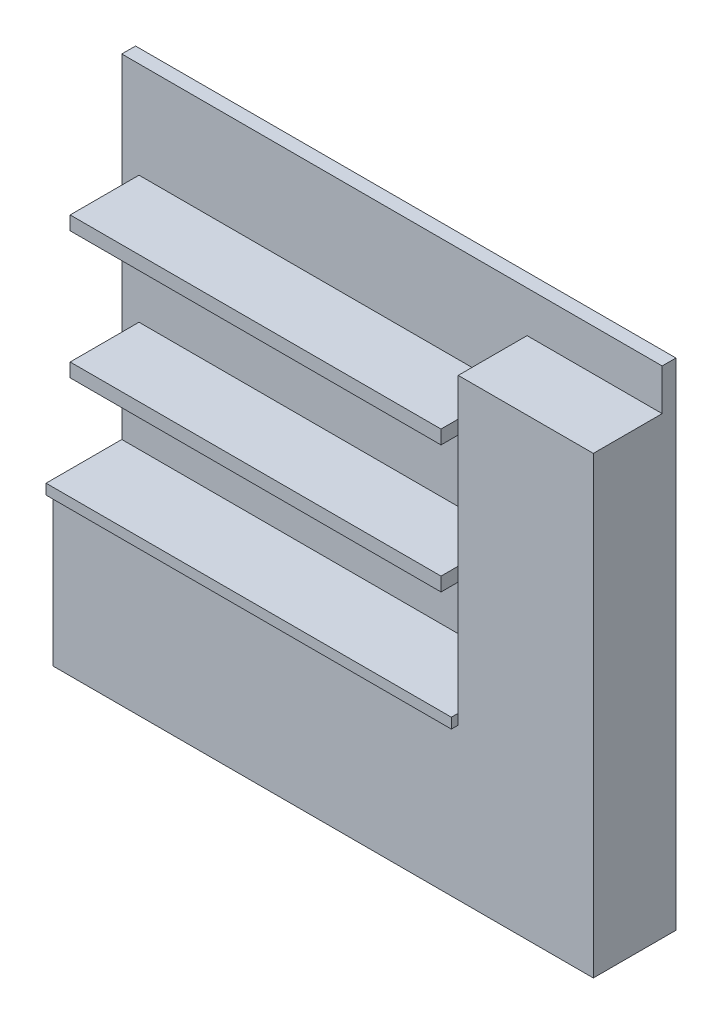
SolidWorks part; units mm, degrees
ref_plane "Front Plane" through (0, 0, 0) normal (0, 0, 1) x (1, 0, 0)
ref_plane "Top Plane" through (0, 0, 0) normal (0, 1, 0) x (1, 0, 0)
ref_plane "Right Plane" through (0, 0, 0) normal (1, 0, 0) x (0, 0, -1)
sketch "Sketch1" plane through (0, 0, 0) normal (0, 0, 1) x (1, 0, 0)
  line L1 (-1993.9, 1828.8) -> (1993.9, 1828.8)
  line L2 (-1993.9, 1828.8) -> (-1993.9, -1828.8)
  line L3 (-1993.9, -1828.8) -> (1993.9, -1828.8)
  line L4 (1993.9, 1828.8) -> (1993.9, -1828.8)
  line L5 (-1993.9, 1828.8) -> (1993.9, -1828.8) construction
  line L6 (-1993.9, -1828.8) -> (1993.9, 1828.8) construction
  point P4 (0, 0)
  dimension "D1" = 3657.6
  dimension "D2" = 3987.8
extrude "Boss-Extrude1" add sketch "Sketch1" along normal blind 101.6
sketch "Sketch2" plane through (0, 0, 101.6) normal (0, 0, 1) x (1, 0, 0)
  line L0 (-1993.9, -1828.8) -> (-1993.9, -711.2)
  line L1 (-1993.9, 1828.8) -> (-1993.9, -1828.8) construction
  line L2 (-1993.9, -711.2) -> (996.95, -711.2)
  line L3 (996.95, -711.2) -> (996.95, 1524)
  line L4 (996.95, 1524) -> (1993.9, 1524)
  line L5 (1993.9, -1828.8) -> (1993.9, 1828.8) construction
  line L6 (1993.9, 1524) -> (1993.9, -1828.8)
  line L7 (1993.9, -1828.8) -> (-1993.9, -1828.8)
  dimension "D1" = 3352.8
  dimension "D2" = 996.95
  dimension "D3" = 1117.6
extrude "Boss-Extrude2" add sketch "Sketch2" along normal blind 508
sketch "Sketch3" plane through (0, 0, 609.6) normal (0, 0, 1) x (1, 0, 0)
  line L0 (-1993.9, -711.2) -> (-1231.9, -711.2)
  line L1 (996.95, -711.2) -> (996.95, -1828.8)
  line L2 (-1993.9, -1828.8) -> (1993.9, -1828.8) construction
  line L3 (-1993.9, -711.2) -> (-1993.9, -1828.8)
  line L4 (-1993.9, -711.2) -> (-1993.9, -1828.8) construction
  line L5 (-1993.9, -1828.8) -> (-1231.9, -1828.8)
  line L6 (-1231.9, -1828.8) -> (-1231.9, -711.2)
  line L7 (-1231.9, -711.2) -> (-774.7, -711.2)
  line L8 (-774.7, -711.2) -> (-774.7, -1828.8)
  line L9 (-774.7, -1828.8) -> (-1231.9, -1828.8)
  line L10 (-774.7, -1828.8) -> (-774.7, -1727.2)
  line L11 (-774.7, -1727.2) -> (996.95, -1727.2)
  line L13 (-774.7, -711.2) -> (-419.1, -711.2)
  line L15 (-419.1, -711.2) -> (-63.5, -711.2)
  line L16 (996.95, -711.2) -> (-1993.9, -711.2) construction
  line L17 (342.9, -711.2) -> (342.9, -1727.2)
  line L18 (-419.1, -711.2) -> (-419.1, -1727.2)
  line L19 (-63.5, -711.2) -> (-63.5, -1727.2)
  line L20 (-63.5, -711.2) -> (342.9, -711.2)
  line L21 (342.9, -914.4) -> (996.95, -914.4)
  line L22 (342.9, -1168.4) -> (996.95, -1168.4)
  line L23 (342.9, -1473.2) -> (996.95, -1473.2)
  dimension "D1" = 101.6
  dimension "D2" = 406.4
  dimension "D3" = 762
  dimension "D4" = 457.2
  dimension "D5" = 355.6
  dimension "D6" = 355.6
  dimension "D7" = 203.2
  dimension "D8" = 254
  dimension "D9" = 304.8
sketch "Sketch4" plane through (0, 0, 101.6) normal (0, 0, 1) x (1, 0, 0)
  line L0 (-1993.9, -711.2) -> (-1993.9, -635)
  line L1 (-1993.9, 1828.8) -> (-1993.9, -711.2) construction
  line L2 (-1993.9, -635) -> (996.95, -635)
  line L3 (996.95, 1524) -> (996.95, -711.2) construction
  line L4 (996.95, -635) -> (996.95, -711.2)
  line L5 (996.95, -711.2) -> (-1993.9, -711.2)
  dimension "D1" = 76.2
extrude "Boss-Extrude3" add sketch "Sketch4" along normal blind 558.8
sketch "Sketch5" plane through (0, 0, 101.6) normal (0, 0, 1) x (1, 0, 0)
  line L0 (-1993.9, -635) -> (-1866.9, -635) construction
  line L1 (996.95, -635) -> (-1993.9, -635) construction
  line L2 (-1866.9, -635) -> (-1866.9, 127) construction
  line L3 (-1866.9, 76.2) -> (-1866.9, 177.8)
  line L4 (-1866.9, 177.8) -> (869.95, 177.8)
  line L5 (869.95, 177.8) -> (869.95, 76.2)
  line L6 (869.95, 76.2) -> (-1866.9, 76.2)
  line L7 (996.95, 1524) -> (996.95, -635) construction
  line L8 (-1993.9, 596.9) -> (996.95, 596.9) construction
  line L10 (-1993.9, 1828.8) -> (-1993.9, -635) construction
  line L11 (869.95, 1117.6) -> (-1866.9, 1117.6)
  line L12 (869.95, 1016) -> (869.95, 1117.6)
  line L13 (-1866.9, 1016) -> (869.95, 1016)
  line L14 (-1866.9, 1117.6) -> (-1866.9, 1016)
  point P9 (-1866.9, 127)
  point P21 (-1866.9, 1066.8)
  dimension "D1" = 127
  dimension "D2" = 101.6
  dimension "D3" = 762
  dimension "D4" = 127
extrude "Boss-Extrude4" add sketch "Sketch5" along normal blind 508
sketch "Sketch6" plane through (0, 0, 609.6) normal (0, 0, 1) x (1, 0, 0)
  line L0 (996.95, -711.2) -> (1993.9, -711.2)
  line L1 (1993.9, -1828.8) -> (1993.9, 1524) construction
  line L2 (1993.9, -711.2) -> (1993.9, -457.2)
  line L3 (1993.9, -457.2) -> (996.95, -457.2)
  line L4 (996.95, 1524) -> (996.95, -635) construction
  line L5 (996.95, -457.2) -> (996.95, -711.2)
  line L6 (1993.9, -711.2) -> (1993.9, -1828.8)
  line L7 (1993.9, -1828.8) -> (996.95, -1828.8)
  line L8 (996.95, 1524) -> (996.95, 1168.4)
  line L9 (996.95, 1524) -> (996.95, -635) construction
  line L10 (996.95, 1168.4) -> (1993.9, 1168.4)
  line L11 (1993.9, 1168.4) -> (1993.9, 1524)
  line L12 (1993.9, 1524) -> (996.95, 1524)
  line L13 (996.95, 1168.4) -> (996.95, -457.2)
  line L14 (996.95, 355.6) -> (1993.9, 355.6)
  line L15 (1495.425, 1168.4) -> (1495.425, -457.2)
  line L16 (996.95, 1168.4) -> (996.95, -457.2)
  line L17 (1993.9, -457.2) -> (1993.9, 1168.4)
  dimension "D1" = 254
  dimension "D2" = 355.6
